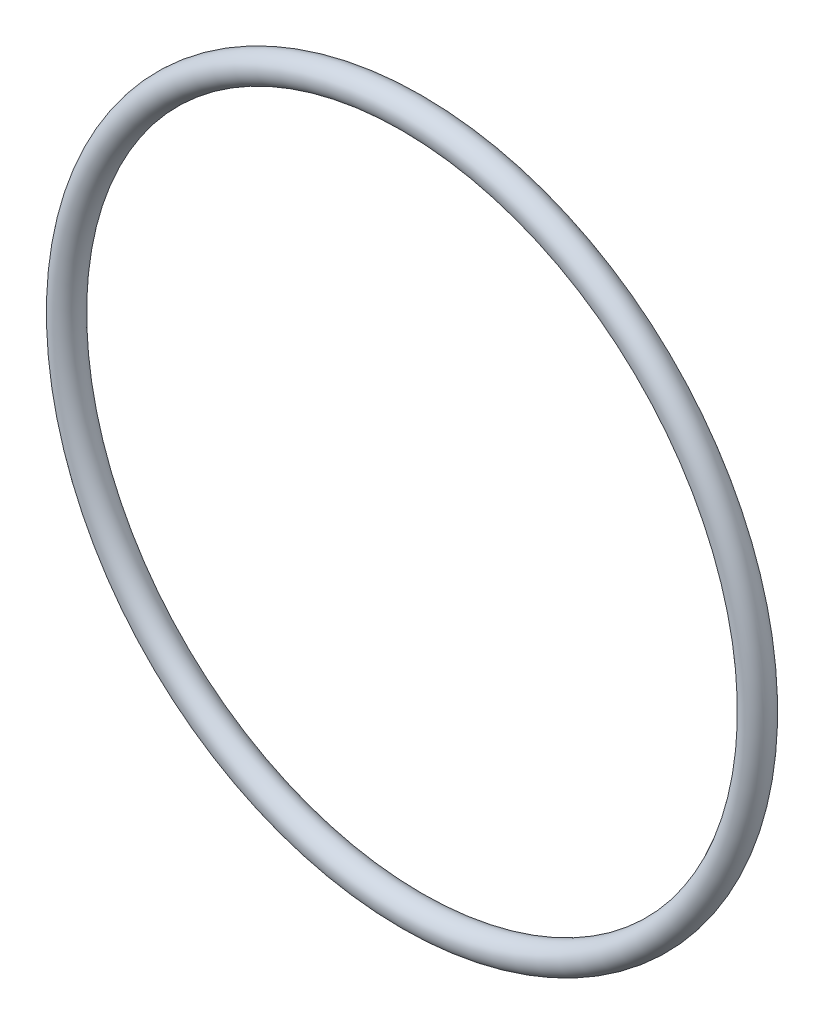
SolidWorks part; units mm, degrees
ref_plane "Front Plane" through (0, 0, 0) normal (0, 0, 1) x (1, 0, 0)
ref_plane "Top Plane" through (0, 0, 0) normal (0, 1, 0) x (1, 0, 0)
ref_plane "Right Plane" through (0, 0, 0) normal (1, 0, 0) x (0, 0, -1)
sketch "Sketch1" plane through (0, 0, 0) normal (1, 0, 0) x (0, 0, -1)
  line L0 (0, -41.0718) -> (0, 41.0718) construction
  circle A0 centre (0, -42.8371) radius 1.7653 construction
  circle A1 centre (0, 42.8371) radius 1.7653 construction
  point P3 (-1.7653, -41.0718)
  point P4 (0, 0)
  point P7 (0, -44.6024)
  point P8 (-1.7653, -42.8371)
  point P9 (1.7653, -42.8371)
  point P12 (0, 44.6024)
  dimension "ID" = 82.1436
  dimension "OD" = 89.2048
  dimension "Width" = 3.5306
sketch "Sketch2" plane through (0, 0, 0) normal (1, 0, 0) x (0, 0, -1)
  line L0 (-41.0718, 0) -> (41.0718, 0) construction
  line L1 (0, -41.0718) -> (0, 41.0718) construction
  circle A0 centre (0, 42.8371) radius 1.7653 construction
  circle A1 centre (0, 42.8371) radius 1.7653
  point P7 (0, 0)
revolve "Revolve1" add sketch "Sketch2" angle 360 about L0
sketch "Drawing Reference 1" plane through (0, 0, 0) normal (0, 0, 1) x (1, 0, 0)
  circle A0 centre (0, 0) radius 44.6024
  circle A1 centre (0, 0) radius 41.0718
sketch "Sketch3" plane through (0, 0, 0) normal (0, 0, 1) x (1, 0, 0)
  circle A0 centre (0, 0) radius 44.6024
  dimension "D1" = 89.2048
